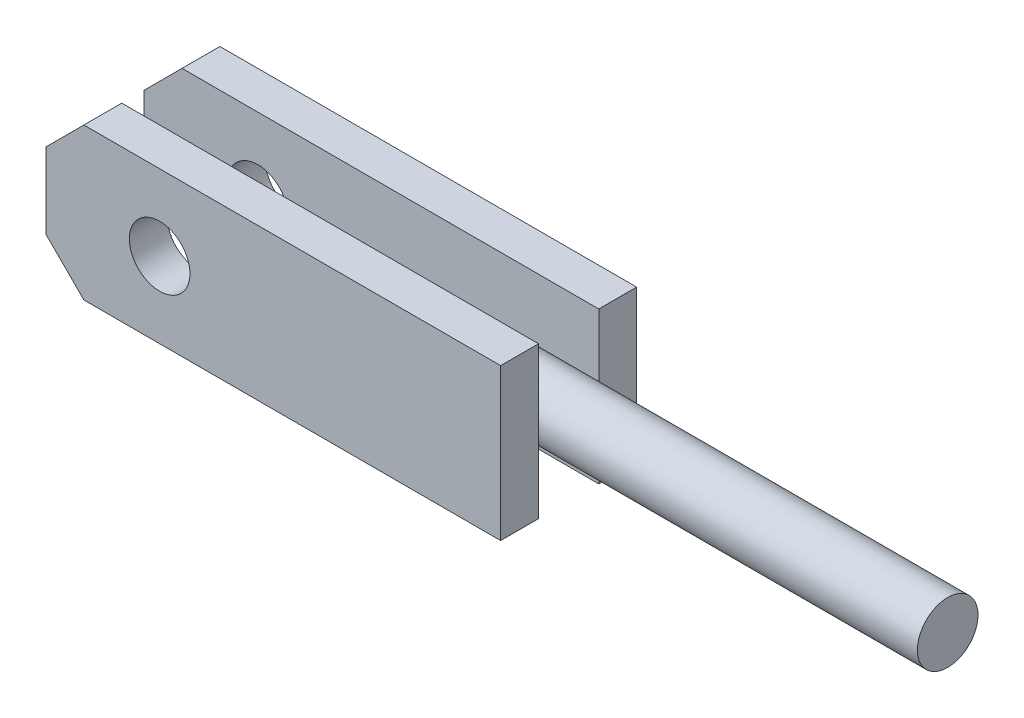
SolidWorks part; units mm, degrees
material "ASTM A36"
ref_plane "Front Plane" through (0, 0, 0) normal (0, 0, 1) x (1, 0, 0)
ref_plane "Top Plane" through (0, 0, 0) normal (0, 1, 0) x (1, 0, 0)
ref_plane "Right Plane" through (0, 0, 0) normal (1, 0, 0) x (0, 0, -1)
sketch "Sketch1" plane through (0, 0, 0) normal (0, 0, 1) x (1, 0, 0)
  line L1 (60, -20) -> (-60, -20)
  line L2 (60, -20) -> (60, 20)
  line L3 (60, 20) -> (-60, 20)
  line L4 (-60, -20) -> (-60, 20)
  line L5 (60, -20) -> (-60, 20) construction
  line L6 (60, 20) -> (-60, -20) construction
  point P0 (0, 0)
  dimension "D1" = 40
  dimension "D2" = 120
extrude "Boss-Extrude1" add sketch "Sketch1" along normal blind 10
sketch "Sketch4" plane through (0, 0, 10) normal (0, 0, 1) x (1, 0, 0)
  line L0 (-60, 20) -> (-60, -20) construction
  circle A0 centre (-30, 0) radius 8
  dimension "D2" = 16
  dimension "D1" = 30
extrude "Cut-Extrude1" cut sketch "Sketch4" against normal blind 10
chamfer "Chamfer2" distance 10 angle 45 1 edges at (-60, 20, 5)
chamfer "Chamfer3" distance 10 angle 45 1 edges at (-60, -20, 5)
sketch "Sketch5" plane through (60, 0, 0) normal (1, 0, 0) x (0, 0, -1)
  line L0 (0, -20) -> (0, 20) construction
  circle A0 centre (8, 0) radius 8
  dimension "D1" = 16
  dimension "D2" = 8
extrude "Boss-Extrude2" add sketch "Sketch5" along normal blind 100 and the other way blind 20 separate body
pattern_linear "LPattern1" count 2 spacing 25.9 along (0, 0, -1) of "Boss-Extrude1"
chamfer "Chamfer4" distance 10 angle 45 1 edges at (-60, 20, -20.9)
chamfer "Chamfer5" distance 10 angle 45 1 edges at (-60, -20, -20.9)
sketch "Sketch6" plane through (0, 0, -25.9) normal (0, 0, -1) x (-1, 0, 0)
  line L0 (60, 10) -> (60, -10) construction
  circle A0 centre (30, 0) radius 8
  dimension "D1" = 30
  dimension "D2" = 16
extrude "Cut-Extrude2" cut sketch "Sketch6" against normal blind 100
